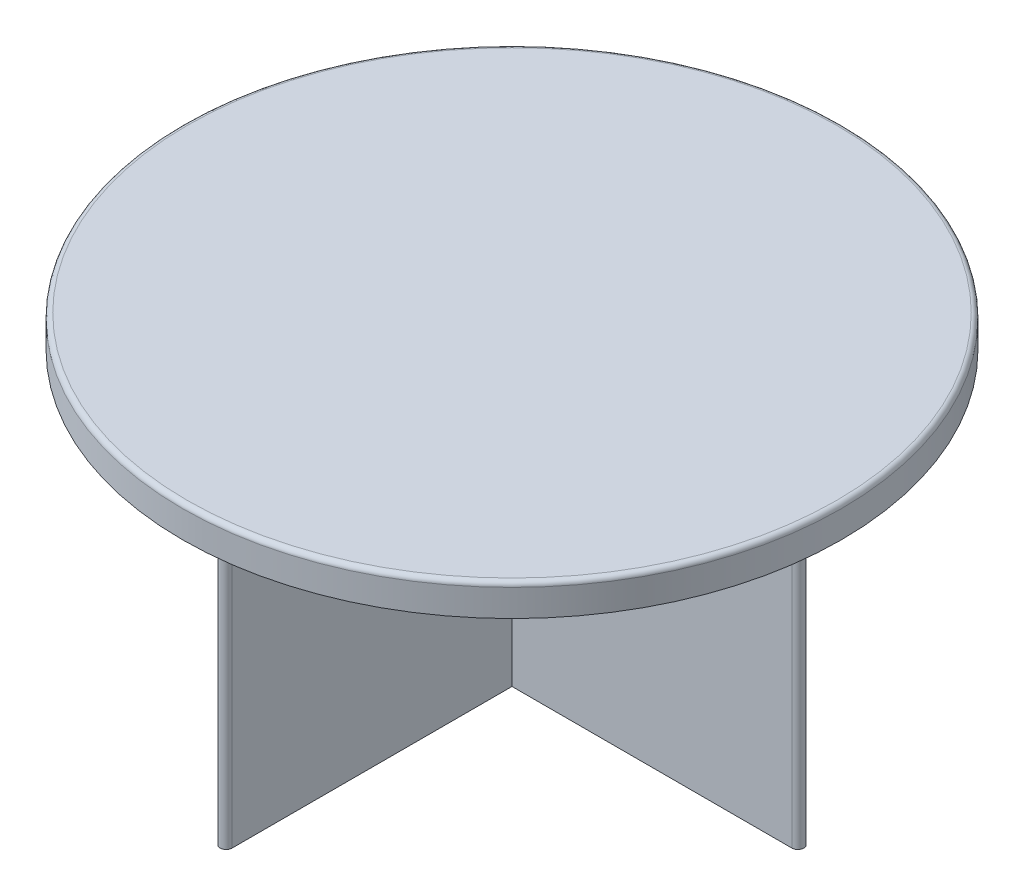
SolidWorks part; units mm, degrees
ref_plane "Front Plane" through (0, 0, 0) normal (0, 0, 1) x (1, 0, 0)
ref_plane "Top Plane" through (0, 0, 0) normal (0, 1, 0) x (1, 0, 0)
ref_plane "Right Plane" through (0, 0, 0) normal (1, 0, 0) x (0, 0, -1)
sketch "Sketch1" plane through (0, 0, 0) normal (0, 1, 0) x (1, 0, 0)
  circle A0 centre (0, 0) radius 527.05
  dimension "D1" = 1054.1
extrude "Boss-Extrude1" add sketch "Sketch1" along normal blind 50.8
fillet "Fillet1" radius 7.62 1 edges at (0, 50.8, 527.05)
sketch "Sketch2" plane through (0, 0, 0) normal (0, -1, 0) x (1, 0, 0)
  line L0 (0, 457.2) -> (0, -457.2) construction
  line L1 (-457.2, 0) -> (457.2, 0) construction
  line L2 (-9.525, 457.2) -> (-9.525, -457.2)
  line L3 (-457.2, -9.525) -> (457.2, -9.525)
  line L4 (9.525, 457.2) -> (9.525, -457.2)
  line L5 (-457.2, 9.525) -> (457.2, 9.525)
  arc A0 (-9.525, 457.2) -> (9.525, 457.2) centre (0, 457.2) cw
  arc A1 (-9.525, -457.2) -> (9.525, -457.2) centre (0, -457.2) ccw
  arc A2 (-457.2, -9.525) -> (-457.2, 9.525) centre (-457.2, 0) cw
  arc A3 (457.2, -9.525) -> (457.2, 9.525) centre (457.2, 0) ccw
  point P5 (0, 0)
  point P6 (0, 0)
  dimension "D1" = 914.4
  dimension "D2" = 914.4
  dimension "D3" = 9.525
  dimension "D4" = 9.525
extrude "Boss-Extrude2" add sketch "Sketch2" along normal blind 457.2 contours L5 A3 L3 A2 | L4 A1 L2 A0
equation "\"D2@Sketch2\"=\"D1@Sketch2\""
